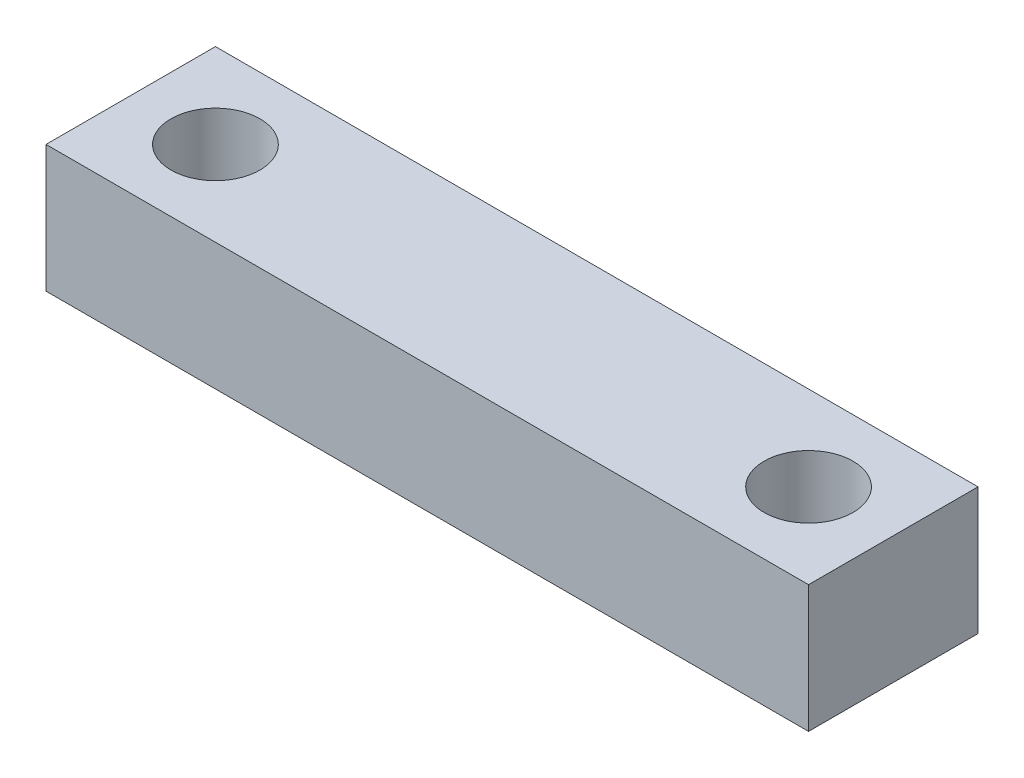
SolidWorks part; units mm, degrees
material "Balsa"
ref_plane "Front Plane" through (0, 0, 0) normal (0, 0, 1) x (1, 0, 0)
ref_plane "Top Plane" through (0, 0, 0) normal (0, 1, 0) x (1, 0, 0)
ref_plane "Right Plane" through (0, 0, 0) normal (1, 0, 0) x (0, 0, -1)
sketch "Sketch1" plane through (0, 0, 0) normal (0, 1, 0) x (1, 0, 0)
  line L1 (0, 0) -> (36, 0)
  line L2 (0, 0) -> (0, -8)
  line L3 (0, -8) -> (36, -8)
  line L4 (36, 0) -> (36, -8)
  line L5 (18, 0) -> (18, -8) construction
  line L6 (0, -4) -> (36, -4) construction
  circle A0 centre (4, -4) radius 2.1
  circle A1 centre (32, -4) radius 2.1
  dimension "D2" = 4.2
  dimension "D1" = 36
  dimension "D3" = 4
  dimension "D4" = 28
  dimension "D5" = 4
extrude "Boss-Extrude1" add sketch "Sketch1" along normal blind 6
